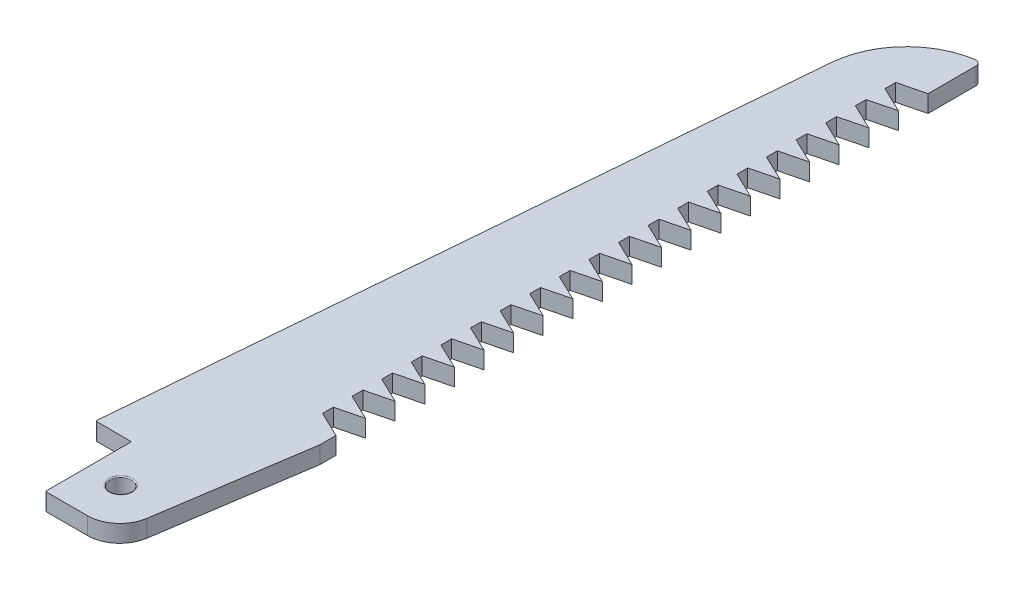
SolidWorks part; units mm, degrees
ref_plane "Front Plane" through (0, 0, 0) normal (0, 0, 1) x (1, 0, 0)
ref_plane "Top Plane" through (0, 0, 0) normal (0, 1, 0) x (1, 0, 0)
ref_plane "Right Plane" through (0, 0, 0) normal (1, 0, 0) x (0, 0, -1)
sketch "Sketch1" plane through (0, 0, 0) normal (0, 1, 0) x (1, 0, 0)
  line L11 (0, 0) -> (0, 6)
  line L12 (0, 0) -> (12.5, 0) construction
  line L13 (0, 0) -> (0, 78) construction
  line L14 (0, 78) -> (12.5, 78) construction
  line L15 (12.5, 0) -> (12.5, 78) construction
  line L16 (0, 6) -> (5.5, 71)
  line L17 (12.5, 78) -> (12.5, 16.5)
  line L18 (12.5, 16.5) -> (10, 0)
  line L19 (10, 0) -> (0, 0)
  arc A1 (5.5, 71) -> (12.5, 78) centre (13.1471, 70.3529) cw
  circle A2 centre (6.5, 4) radius 1
  dimension "D8" = 2
  dimension "D1" = 78
  dimension "D2" = 12.5
  dimension "D3" = 10
  dimension "D4" = 6
  dimension "D5" = 7
  dimension "D6" = 7
  dimension "D7" = 61.5
  dimension "D9" = 4
  dimension "D10" = 6.5
extrude "Boss-Extrude2" add sketch "Sketch1" along normal blind 1.6
sketch "Sketch3" plane through (0, 1.6, 0) normal (0, 1, 0) x (1, 0, 0)
  line L1 (0, 0) -> (3.5, 0)
  line L2 (0, 0) -> (0, 8)
  line L3 (0, 8) -> (3.5, 8)
  line L4 (3.5, 0) -> (3.5, 8)
  dimension "D1" = 3.5
  dimension "D2" = 8
extrude "Cut-Extrude2" cut sketch "Sketch3" against normal through all
fillet "Fillet2" radius 3 1 edges at (10, 0.8, 0)
fillet "Fillet3" radius 0.1 2 edges at (6.5, 1.6, -3) (6.5, 0, -3)
fillet "Fillet4" radius 0.1 3 edges at (0.1692, 0.8, -8) (3.5, 0.8, -8) (3.5, 0.8, 0)
sketch "Sketch4" plane through (0, 1.6, 0) normal (0, 1, 0) x (1, 0, 0)
  line L0 (12.5, 73) -> (10.1, 72.3983)
  line L1 (12.5, 16.5) -> (12.5, 78) construction
  line L2 (10.1, 72.3983) -> (10.1, 71.3983)
  line L3 (10.1, 71.3983) -> (12.5, 70.25)
  line L4 (12.5, 73) -> (12.5, 70.25)
  point P4 (12.5, 70.25)
  point P7 (12.5, 73)
  point P9 (10.1, 72.3983)
  dimension "D1" = 1
  dimension "D2" = 2.4
  dimension "D3" = 2.75
  dimension "D4" = 5
extrude "Cut-Extrude3" cut sketch "Sketch4" against normal through all
pattern_linear "LPattern7" count 20 spacing 2.75 along (0, 0, 1) of "Cut-Extrude3"
fillet "Fillet5" radius 0.5 1 edges at (12.5, 0.8, -78)
